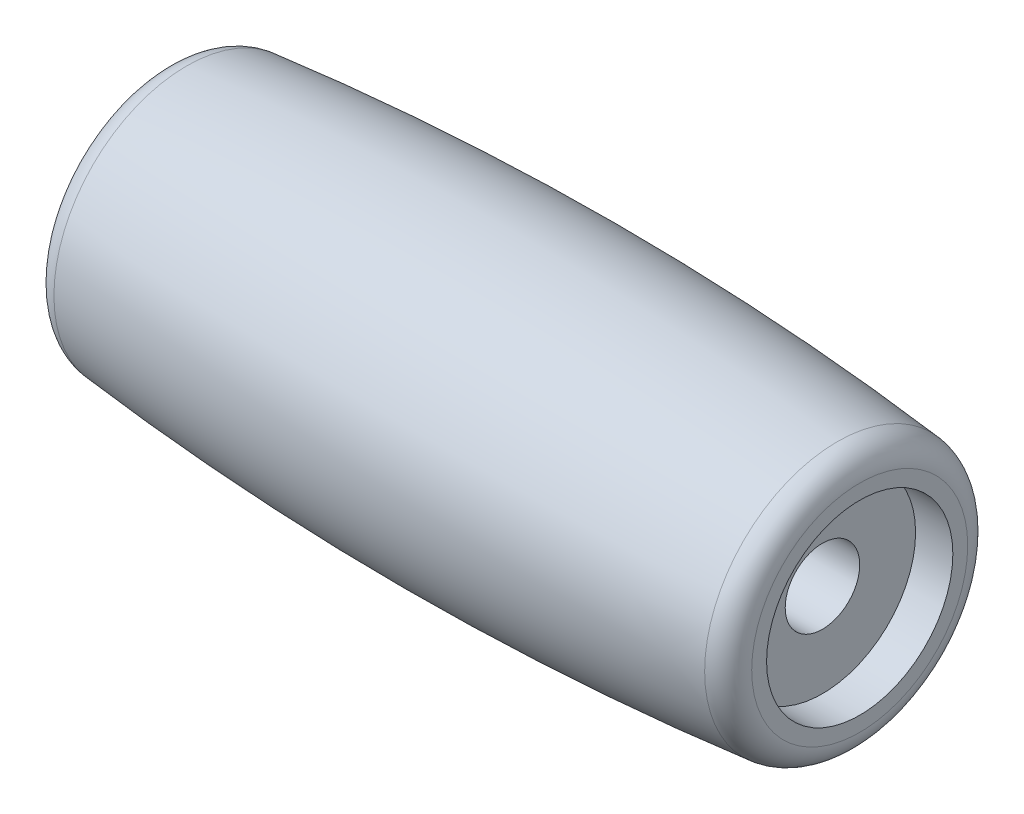
SolidWorks part; units mm, degrees
ref_plane "Plan de face" through (0, 0, 0) normal (0, 0, 1) x (1, 0, 0)
ref_plane "Plan de dessus" through (0, 0, 0) normal (0, 1, 0) x (1, 0, 0)
ref_plane "Plan de droite" through (0, 0, 0) normal (1, 0, 0) x (0, 0, -1)
sketch "Esquisse1" plane through (0, 0, 0) normal (0, 0, 1) x (1, 0, 0)
  line L0 (0, 6) -> (0, 0) construction
  line L1 (0, 0) -> (7.9862, 0) construction
  line L2 (-12.5, 1.5) -> (12.5, 1.5)
  line L3 (12.5, 1.5) -> (12.5, 3.75)
  line L4 (12.5, 3.75) -> (14, 3.75)
  line L5 (14, 3.75) -> (14, 4.3486)
  line L6 (-14, 3.75) -> (-14, 4.3486)
  line L7 (-12.5, 3.75) -> (-14, 3.75)
  line L8 (-12.5, 1.5) -> (-12.5, 3.75)
  arc A0 (-13.1, 5.3436) -> (13.1, 5.3436) centre (0, -125.0417) cw
  arc A1 (14, 4.3486) -> (13.1, 5.3436) centre (13, 4.3486) ccw
  arc A2 (-14, 4.3486) -> (-13.1, 5.3436) centre (-13, 4.3486) cw
  point P14 (0, 1.5)
  point P16 (14, 5.25)
  point P19 (-14, 5.25)
  dimension "D7" = 1
  dimension "D1" = 1.5
  dimension "D2" = 3.75
  dimension "D3" = 1.5
  dimension "D4" = 1.5
  dimension "D5" = 14
  dimension "D6" = 6
revolve "Révolution1" add sketch "Esquisse1" angle 360 about L1
